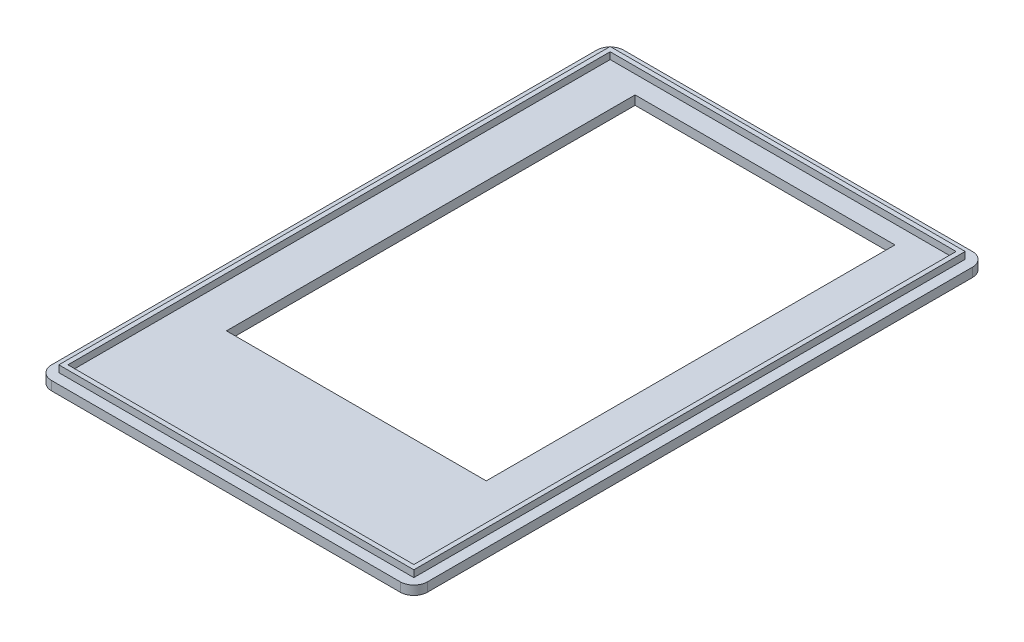
SolidWorks part; units mm, degrees
ref_plane "Front Plane" through (0, 0, 0) normal (0, 0, 1) x (1, 0, 0)
ref_plane "Top Plane" through (0, 0, 0) normal (0, 1, 0) x (1, 0, 0)
ref_plane "Right Plane" through (0, 0, 0) normal (1, 0, 0) x (0, 0, -1)
sketch "Sketch1" plane through (0, 0, 0) normal (0, 1, 0) x (1, 0, 0)
  line L0 (0, 61.175) -> (0, -61.175) construction
  line L1 (-39.5, 61.175) -> (39.5, 61.175)
  line L2 (-39.5, 61.175) -> (-39.5, -61.175)
  line L3 (-39.5, -61.175) -> (39.5, -61.175)
  line L4 (39.5, 61.175) -> (39.5, -61.175)
  line L7 (-39, -60.675) -> (-39, -61.175) construction
  line L8 (-28.99, 56.175) -> (28.99, 56.175) construction
  line L9 (-28.99, 56.175) -> (-28.99, -34.675) construction
  line L10 (-28.99, -34.675) -> (28.99, -34.675) construction
  line L11 (28.99, 56.175) -> (28.99, -34.675) construction
  line L12 (-39, -39.675) -> (39, -39.675)
  line L13 (-39, -39.675) -> (-39, -60.675)
  line L14 (-39, -60.675) -> (39, -60.675)
  line L15 (39, -39.675) -> (39, -60.675)
  line L16 (-39, -60.675) -> (-39.5, -60.675) construction
  line L19 (-41.5, 63.175) -> (41.5, 63.175)
  line L20 (41.5, 63.175) -> (41.5, -63.175)
  line L21 (-41.5, -63.175) -> (41.5, -63.175)
  line L22 (-41.5, 63.175) -> (-41.5, -63.175)
  line L23 (-28.69, 55.875) -> (28.69, 55.875)
  line L24 (28.69, 55.875) -> (28.69, -34.375)
  line L25 (-28.69, -34.375) -> (28.69, -34.375)
  line L26 (-28.69, 55.875) -> (-28.69, -34.375)
  point P0 (0, 0)
  point P17 (0, 0)
  dimension "D1" = 90.85
  dimension "D2" = 57.98
  dimension "D3" = 78
  dimension "D4" = 21
  dimension "D5" = 0.5
  dimension "D6" = 5
  dimension "D7" = 5
  dimension "D8" = 2
  dimension "D9" = 0.3
extrude "Boss-Extrude1" add sketch "Sketch1" along normal blind 2 contours L19 L20 L21 L22 | L8 L11 L10 L9 | L23 L24 L25 L26
sketch "Sketch2" plane through (0, 2, 0) normal (0, 1, 0) x (1, 0, 0)
  line L4 (-38.2, 59.875) -> (-38.2, -59.875)
  line L5 (-38.2, -59.875) -> (38.2, -59.875)
  line L6 (38.2, -59.875) -> (38.2, 59.875)
  line L7 (38.2, 59.875) -> (-38.2, 59.875)
  line L8 (-39.2, 60.875) -> (-39.2, -60.875)
  line L9 (-39.2, -60.875) -> (39.2, -60.875)
  line L10 (39.2, -60.875) -> (39.2, 60.875)
  line L11 (39.2, 60.875) -> (-39.2, 60.875)
  line L12 (-39.2, 60.875) -> (-39.2, -60.875)
  line L13 (-39.2, -60.875) -> (39.2, -60.875)
  line L14 (39.2, -60.875) -> (39.2, 60.875)
  line L15 (39.2, 60.875) -> (-39.2, 60.875)
  dimension "D1" = 2.3
  dimension "D2" = 1
extrude "Boss-Extrude2" add sketch "Sketch2" along normal blind 1.5
fillet "Fillet1" radius 3 4 edges at (-41.5, 1, -63.175) (41.5, 1, -63.175) (41.5, 1, 63.175) (-41.5, 1, 63.175)
